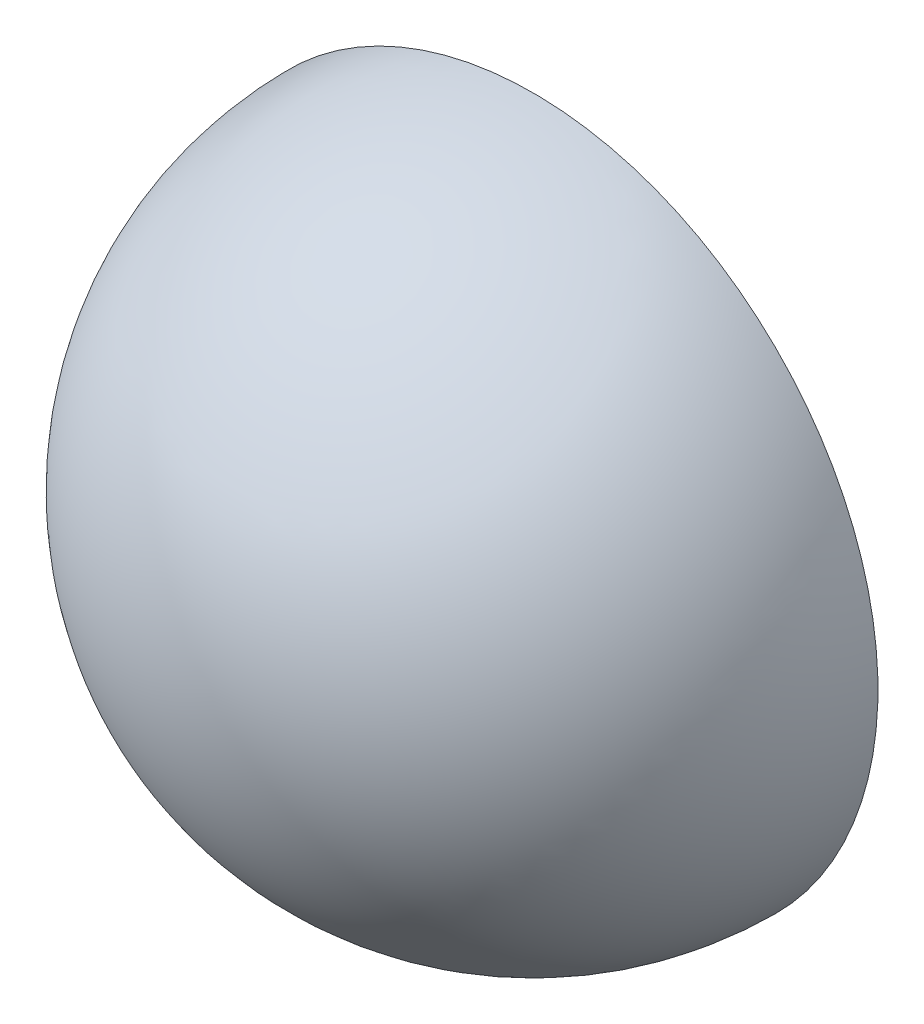
SolidWorks part; units mm, degrees
ref_plane "正面" through (0, 0, 0) normal (0, 0, 1) x (1, 0, 0)
ref_plane "平面" through (0, 0, 0) normal (0, 1, 0) x (1, 0, 0)
ref_plane "右側面" through (0, 0, 0) normal (1, 0, 0) x (0, 0, -1)
sketch "ｽｹｯﾁ1" plane through (0, 0, 0) normal (0, 0, 1) x (1, 0, 0)
  line L0 (-13.65, 0) -> (13.65, 0) construction
  line L1 (-13.65, 0) -> (13.65, 0)
  arc A1 (-13.65, 0) -> (13.65, 0) centre (0, 0) cw
  dimension "D1" = 13.65
revolve "回転6" add sketch "ｽｹｯﾁ1" angle 180 about L0
